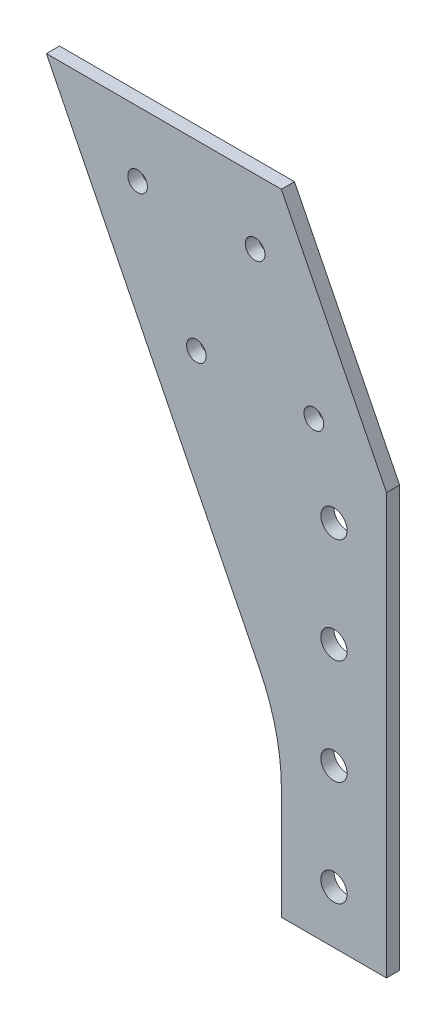
SolidWorks part; units mm, degrees
material "6063-T1"
ref_plane "Front Plane" through (0, 0, 0) normal (0, 0, 1) x (1, 0, 0)
ref_plane "Top Plane" through (0, 0, 0) normal (0, 1, 0) x (1, 0, 0)
ref_plane "Right Plane" through (0, 0, 0) normal (1, 0, 0) x (0, 0, -1)
sketch "Sketch1" plane through (0, 0, 0) normal (0, 0, 1) x (1, 0, 0)
  line L0 (12.7, 25.4) -> (-25.4082, 101.6)
  line L1 (-12.7, 76.2) -> (12.7, 76.2)
  line L2 (-12.7, 76.2) -> (-12.7, -76.2)
  line L3 (-12.7, -76.2) -> (12.7, -76.2)
  line L4 (12.7, 76.2) -> (12.7, -76.2)
  line L5 (-12.7, 76.2) -> (12.7, -76.2) construction
  line L6 (-12.7, -76.2) -> (12.7, 76.2) construction
  line L7 (-25.4082, 101.6) -> (-50.8082, 101.6)
  line L8 (-50.8082, 101.6) -> (-12.7, 25.4)
  line L9 (-82.2068, 101.6) -> (-12.7, -37.3836)
  line L10 (-82.2068, 101.6) -> (-50.8082, 101.6)
  point P0 (0, 0)
  dimension "D1" = 25.4
  dimension "D2" = 152.4
  dimension "D3" = 153.43
  dimension "D4" = 101.6
  dimension "D5" = 101.6
  dimension "D6" = 25.4
  dimension "D7" = 50.8
extrude "Boss-Extrude1" add sketch "Sketch1" along normal blind 3.175 contours L7 L8 L2 | L4 L0 L1 L2 L3 | L10 L9 L2 L8
fillet "Fillet1" radius 50.8 1 edges at (-12.7, -37.3836, 1.5875)
sketch "Sketch2" plane through (0, 0, 0) normal (0, 0, -1) x (-1, 0, 0)
  line L0 (12.7, -76.2) -> (-12.7, -76.2) construction
  line L1 (12.7, -49.3782) -> (12.7, -76.2) construction
  circle A0 centre (0, -63.5) radius 3.175
  circle A1 centre (0, -38.1) radius 3.175
  circle A2 centre (0, -12.7) radius 3.175
  circle A3 centre (0, 12.7) radius 3.175
  point P10 (0, 0)
  point P11 (0, 0)
  point P12 (-1.8001, -63.5)
  dimension "D1" = 6.35
  dimension "D2" = 6.35
  dimension "D3" = 6.35
  dimension "D4" = 6.35
  dimension "D5" = 12.7
  dimension "D6" = 25.4
  dimension "D7" = 12.7
  dimension "D8" = 25.4
  dimension "D9" = 25.4
extrude "Cut-Extrude1" cut sketch "Sketch2" against normal through all
sketch "Sketch3" plane through (0, 0, 0) normal (0, 0, -1) x (-1, 0, 0)
  line L0 (82.2068, 101.6) -> (18.0651, -26.6558) construction
  line L1 (-12.7, 25.4) -> (25.4082, 101.6) construction
  line L2 (25.4082, 101.6) -> (82.2068, 101.6) construction
  circle A0 centre (33.2565, 88.9) radius 2.3812
  circle A1 centre (61.6558, 88.9) radius 2.3813
  circle A2 centre (19.055, 60.5032) radius 2.3812
  circle A3 centre (47.4543, 60.5032) radius 2.3813
  circle A4 centre (4.8535, 32.1063) radius 2.3812
  circle A5 centre (33.2528, 32.1063) radius 2.3813
  dimension "D1" = 4.7625
  dimension "D2" = 4.7625
  dimension "D3" = 12.7
  dimension "D4" = 12.7
  dimension "D5" = 12.7
  dimension "D6" = 3
extrude "Cut-Extrude2" cut sketch "Sketch3" against normal through all
sketch "Sketch4" plane through (0, 0, 0) normal (0, 0, -1) x (-1, 0, 0)
  line L0 (25.4082, 101.6) -> (82.2068, 101.6) construction
  line L1 (-17.2591, 76.2) -> (131.0707, 76.2)
  line L2 (-17.2591, 76.2) -> (-17.2591, 118.7085)
  line L3 (-17.2591, 118.7085) -> (131.0707, 118.7085)
  line L4 (131.0707, 76.2) -> (131.0707, 118.7085)
  dimension "D1" = 25.4
extrude "Cut-Extrude3" cut sketch "Sketch4" against normal through all
